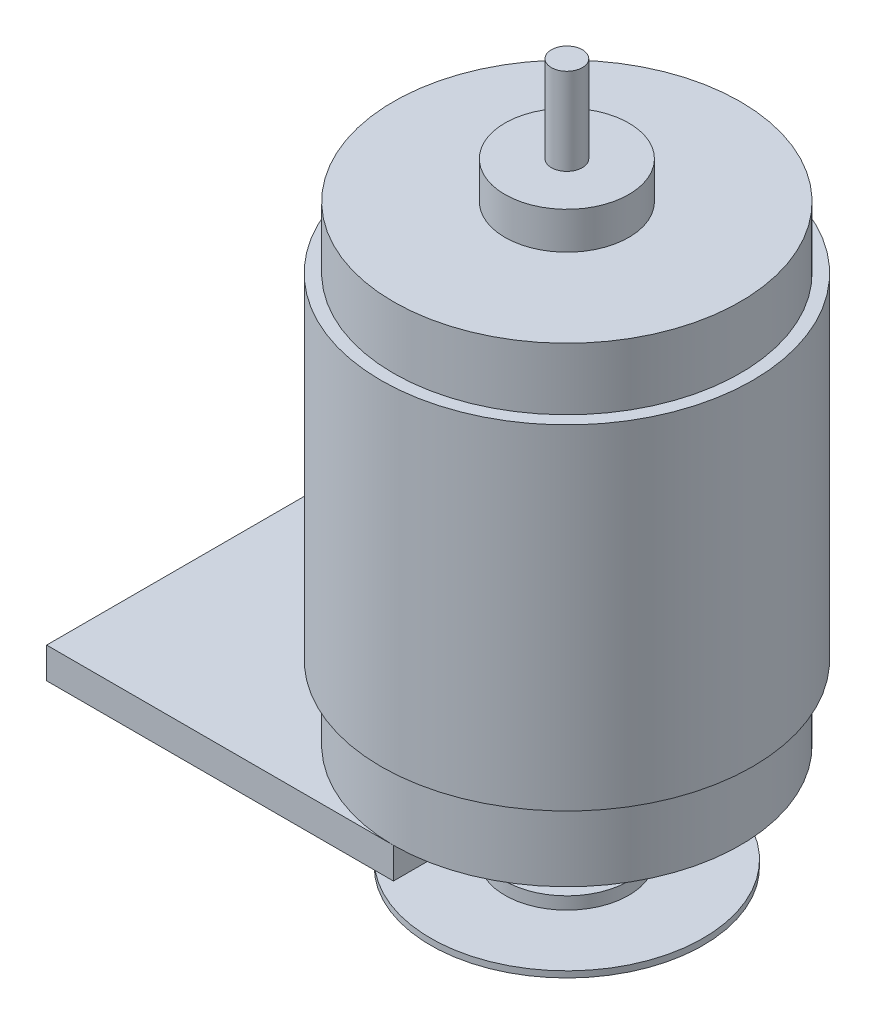
SolidWorks part; units mm, degrees
material "AISI 304"
ref_plane "Front Plane" through (0, 0, 0) normal (0, 0, 1) x (1, 0, 0)
ref_plane "Top Plane" through (0, 0, 0) normal (0, 1, 0) x (1, 0, 0)
ref_plane "Right Plane" through (0, 0, 0) normal (1, 0, 0) x (0, 0, -1)
sketch "Sketch1" plane through (0, 0, 0) normal (0, 1, 0) x (1, 0, 0)
  circle A0 centre (0, 0) radius 15
  dimension "D1" = 30
extrude "Boss-Extrude1" add sketch "Sketch1" along normal blind 27
sketch "Sketch2" plane through (0, 27, 0) normal (0, 1, 0) x (1, 0, 0)
  circle A0 centre (0, 0) radius 14
  dimension "D1" = 28
extrude "Boss-Extrude2" add sketch "Sketch2" along normal blind 5
sketch "Sketch3" plane through (0, 32, 0) normal (0, 1, 0) x (1, 0, 0)
  circle A0 centre (0, 0) radius 5
  dimension "D1" = 10
extrude "Boss-Extrude3" add sketch "Sketch3" along normal blind 3
sketch "Sketch4" plane through (0, 35, 0) normal (0, 1, 0) x (1, 0, 0)
  circle A0 centre (0, 0) radius 1.25
  dimension "D1" = 2.5
extrude "Boss-Extrude4" add sketch "Sketch4" along normal blind 7
sketch "Sketch5" plane through (0, 0, 0) normal (0, -1, 0) x (1, 0, 0)
  circle A0 centre (0, 0) radius 14
  dimension "D1" = 28
extrude "Boss-Extrude5" add sketch "Sketch5" along normal blind 6
sketch "Sketch6" plane through (0, -6, 0) normal (0, -1, 0) x (1, 0, 0)
  circle A0 centre (0, 0) radius 5
  dimension "D1" = 10
extrude "Boss-Extrude6" add sketch "Sketch6" along normal blind 3
sketch "Sketch7" plane through (0, -6, 0) normal (0, -1, 0) x (1, 0, 0)
  line L1 (0, 14) -> (-28, 14)
  line L2 (0, 14) -> (0, -14)
  line L3 (0, -14) -> (-28, -14)
  line L4 (-28, 14) -> (-28, -14)
  circle A0 centre (0, 0) radius 14 construction
  circle A1 centre (0, 0) radius 14 construction
  dimension "D1" = 28
  dimension "D2" = 28
extrude "Boss-Extrude7" add sketch "Sketch7" along normal blind 2.5
sketch "Sketch8" plane through (0, -9, 0) normal (0, -1, 0) x (1, 0, 0)
  circle A0 centre (0, 0) radius 1.25
  dimension "D1" = 2.5
extrude "Boss-Extrude8" add sketch "Sketch8" along normal blind 4
sketch "Sketch9" plane through (0, -13, 0) normal (0, -1, 0) x (1, 0, 0)
  circle A0 centre (0, 0) radius 5
  dimension "D1" = 10
extrude "Boss-Extrude9" add sketch "Sketch9" along normal blind 1
sketch "Sketch10" plane through (0, -14, 0) normal (0, -1, 0) x (1, 0, 0)
  circle A0 centre (0, 0) radius 11
  dimension "D1" = 22
extrude "Boss-Extrude10" add sketch "Sketch10" along normal blind 0.5
sketch "Sketch11" plane through (0, -14.5, 0) normal (0, -1, 0) x (1, 0, 0)
  circle A0 centre (0, 0) radius 5
  dimension "D1" = 10
extrude "Boss-Extrude11" add sketch "Sketch11" along normal blind 1
sketch "Sketch12" plane through (0, -15.5, 0) normal (0, -1, 0) x (1, 0, 0)
  circle A0 centre (0, 0) radius 1.25
  dimension "D1" = 2.5
extrude "Boss-Extrude12" add sketch "Sketch12" along normal blind 3
